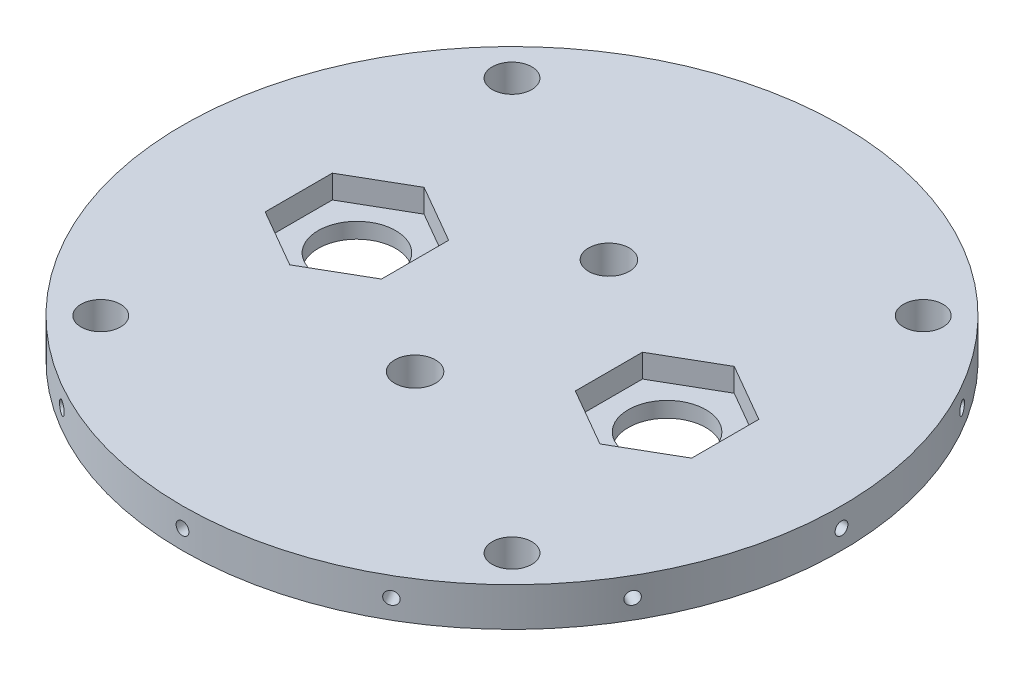
SolidWorks part; units mm, degrees
material "6063-T6"
ref_plane "Płaszczyzna przednia" through (0, 0, 0) normal (0, 0, 1) x (1, 0, 0)
ref_plane "Płaszczyzna górna" through (0, 0, 0) normal (0, 1, 0) x (1, 0, 0)
ref_plane "Płaszczyzna prawa" through (0, 0, 0) normal (1, 0, 0) x (0, 0, -1)
sketch "Szkic1" plane through (0, 0, 0) normal (0, 1, 0) x (1, 0, 0)
  circle A0 centre (0, 0) radius 85
  dimension "D1" = 170
extrude "Dodanie-wyciągnięcie1" add sketch "Szkic1" along normal blind 10
sketch "Szkic2" plane through (0, 10, 0) normal (0, 1, 0) x (1, 0, 0)
  line L0 (0, 0) -> (0, 75) construction
  line L1 (25, 8.6603) -> (40, 17.3205)
  line L2 (-40, 17.3205) -> (-55, 8.6603)
  line L3 (-55, 8.6603) -> (-55, -8.6603)
  line L4 (-55, -8.6603) -> (-40, -17.3205)
  line L5 (-40, -17.3205) -> (-25, -8.6603)
  line L6 (-25, -8.6603) -> (-25, 8.6603)
  line L7 (-25, 8.6603) -> (-40, 17.3205)
  line L8 (25, -8.6603) -> (25, 8.6603)
  line L9 (40, -17.3205) -> (25, -8.6603)
  line L10 (55, -8.6603) -> (40, -17.3205)
  line L11 (55, 8.6603) -> (55, -8.6603)
  line L12 (40, 17.3205) -> (55, 8.6603)
  circle A0 centre (-40, 0) radius 10
  circle A7 centre (0, 0) radius 75 construction
  circle A15 centre (0, 25) radius 5.25
  circle A17 centre (53.033, 53.033) radius 5.1
  circle A19 centre (53.033, -53.033) radius 5.1
  circle A21 centre (-53.033, -53.033) radius 5.1
  circle A23 centre (-53.033, 53.033) radius 5.1
  circle A24 centre (0, -25) radius 5.25
  circle A25 centre (-40, 0) radius 15 construction
  circle A26 centre (40, 0) radius 15 construction
  circle A27 centre (40, 0) radius 10
  point P15 (0, 0)
  point P25 (0, 0)
  dimension "D1" = 25
  dimension "D3" = 2
  dimension "D4" = 40
  dimension "D5" = 30
extrude "Cut-Extrude1" cut sketch "Szkic2" against normal up to next contours A23 | A17 | A21 | A24 | A15 | A19 | A0 | A27
sketch "Sketch1" plane through (0, 10, 0) normal (0, 1, 0) x (1, 0, 0)
  line L6 (-40, 17.3205) -> (-55, 8.6603)
  line L7 (-55, 8.6603) -> (-55, -8.6603)
  line L8 (-55, -8.6603) -> (-40, -17.3205)
  line L9 (-40, -17.3205) -> (-25, -8.6603)
  line L10 (-25, -8.6603) -> (-25, 8.6603)
  line L11 (-25, 8.6603) -> (-40, 17.3205)
  line L12 (-40, 17.3205) -> (-55, 8.6603)
  line L13 (-55, 8.6603) -> (-55, -8.6603)
  line L14 (-55, -8.6603) -> (-40, -17.3205)
  line L15 (-40, -17.3205) -> (-25, -8.6603)
  line L16 (-25, -8.6603) -> (-25, 8.6603)
  line L17 (-25, 8.6603) -> (-40, 17.3205)
  line L18 (55, -8.6603) -> (55, 8.6603)
  line L19 (55, 8.6603) -> (40, 17.3205)
  line L20 (40, 17.3205) -> (25, 8.6603)
  line L21 (25, 8.6603) -> (25, -8.6603)
  line L22 (25, -8.6603) -> (40, -17.3205)
  line L23 (40, -17.3205) -> (55, -8.6603)
  line L24 (55, -8.6603) -> (55, 8.6603)
  line L25 (55, 8.6603) -> (40, 17.3205)
  line L26 (40, 17.3205) -> (25, 8.6603)
  line L27 (25, 8.6603) -> (25, -8.6603)
  line L28 (25, -8.6603) -> (40, -17.3205)
  line L29 (40, -17.3205) -> (55, -8.6603)
  circle A1 centre (0, -25) radius 5.25
  circle A2 centre (0, -25) radius 5.25
  circle A3 centre (53.033, -53.033) radius 5.1
  circle A4 centre (53.033, -53.033) radius 5.1
  circle A5 centre (53.033, 53.033) radius 5.1
  circle A6 centre (53.033, 53.033) radius 5.1
  circle A7 centre (0, 25) radius 5.25
  circle A8 centre (0, 25) radius 5.25
  circle A9 centre (-53.033, 53.033) radius 5.1
  circle A10 centre (-53.033, 53.033) radius 5.1
  circle A11 centre (-53.033, -53.033) radius 5.1
  circle A12 centre (-53.033, -53.033) radius 5.1
  dimension "D1" = 0
  dimension "D2" = 0
  dimension "D3" = 0
  dimension "D4" = 0
  dimension "D5" = 0
  dimension "D6" = 0
  dimension "D7" = 0
  dimension "D8" = 0
extrude "Cut-Extrude2" cut sketch "Sketch1" against normal blind 6 contours L16 L17 L12 L13 L14 L15 | L28 L29 L24 L25 L26 L27
ref_plane "Plane1" through (-85, 0, 0) normal (-1, 0, 0) x (0, 0, 1)
sketch "Sketch2" plane through (-85, 0, 0) normal (-1, 0, 0) x (0, 0, 1)
  line L0 (0, 0) -> (0, 5) construction
  circle A0 centre (0, 5) radius 1.65
  dimension "D1" = 3.3
extrude "Cut-Extrude3" cut sketch "Sketch2" against normal blind 12
pattern_circular "CirPattern1" count 12 over 360 about axis through (0, 0, 0) along (0, 1, 0) of "Cut-Extrude3"
